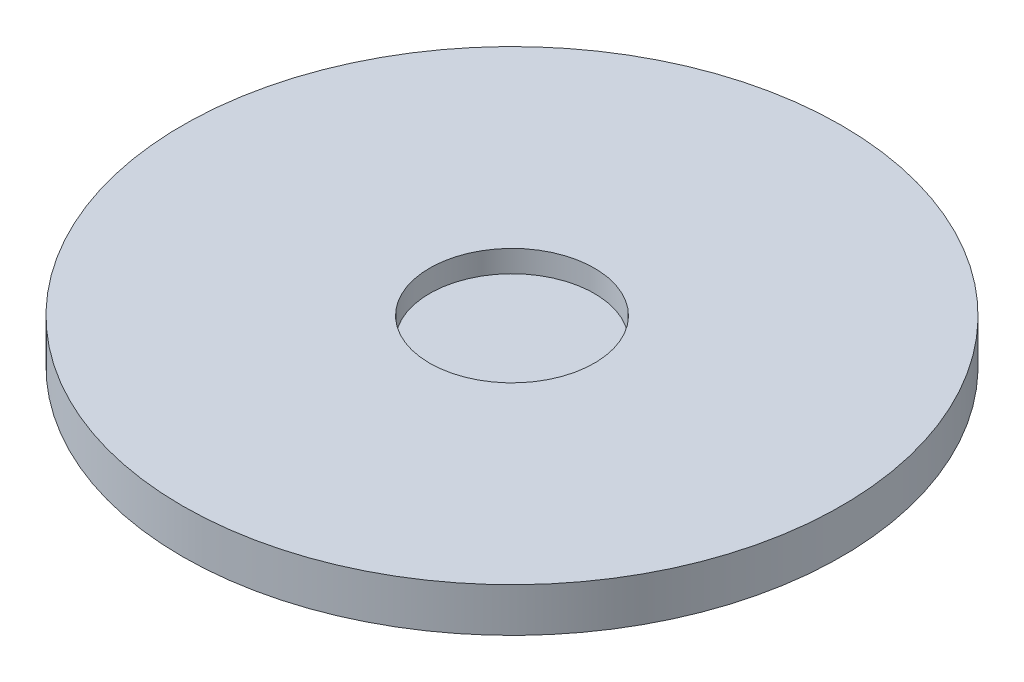
SolidWorks part; units mm, degrees
ref_plane "Front Plane" through (0, 0, 0) normal (0, 0, 1) x (1, 0, 0)
ref_plane "Top Plane" through (0, 0, 0) normal (0, 1, 0) x (1, 0, 0)
ref_plane "Right Plane" through (0, 0, 0) normal (1, 0, 0) x (0, 0, -1)
sketch "Sketch1" plane through (0, 0, 0) normal (0, 1, 0) x (1, 0, 0)
  circle A0 centre (0, 0) radius 150
  dimension "D1" = 300
extrude "Boss-Extrude1" add sketch "Sketch1" along normal blind 20
sketch "Sketch2" plane through (0, 20, 0) normal (0, 1, 0) x (1, 0, 0)
  circle A0 centre (0, 0) radius 37.5
  dimension "D1" = 75
extrude "Cut-Extrude1" cut sketch "Sketch2" against normal blind 10
